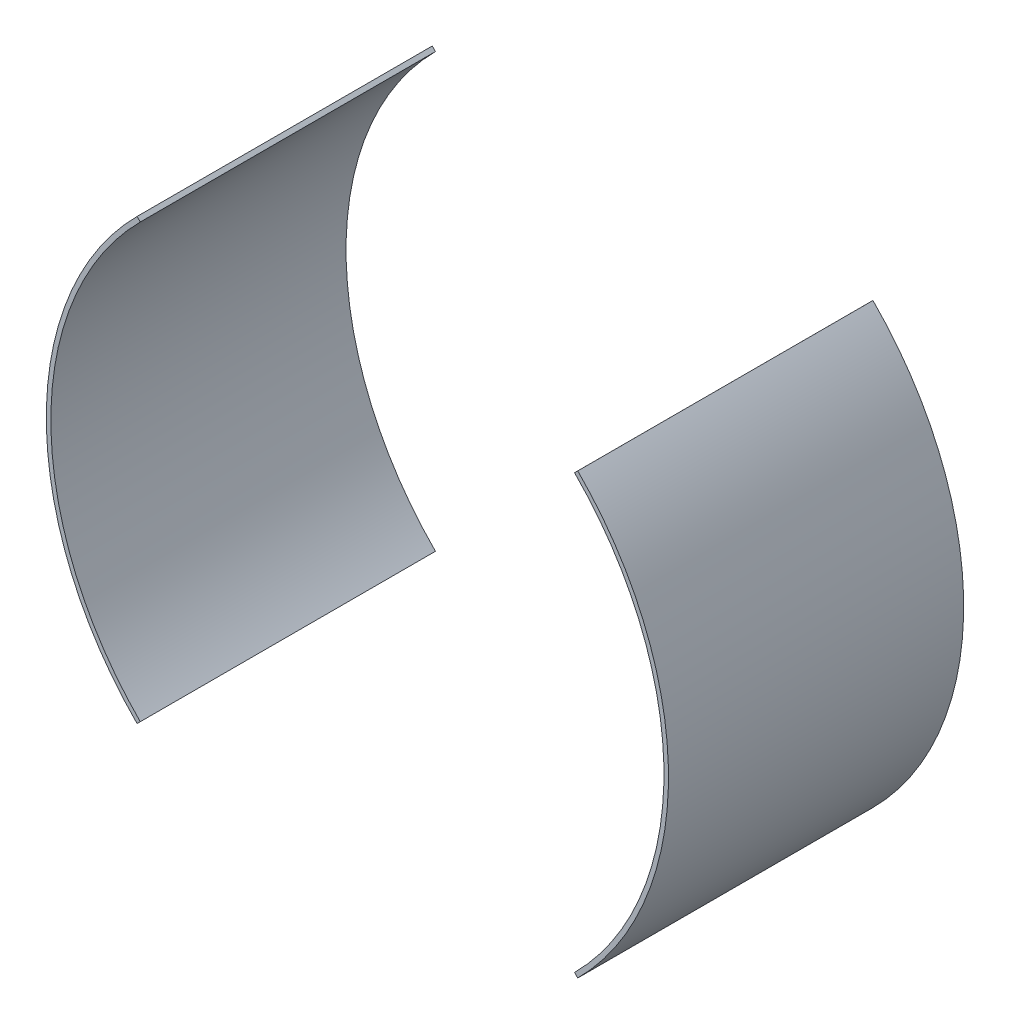
SolidWorks part; units mm, degrees
material "Brass"
ref_plane "Front Plane" through (0, 0, 0) normal (0, 0, 1) x (1, 0, 0)
ref_plane "Top Plane" through (0, 0, 0) normal (0, 1, 0) x (1, 0, 0)
ref_plane "Right Plane" through (0, 0, 0) normal (1, 0, 0) x (0, 0, -1)
sketch "Sketch1" plane through (0, 0, 0) normal (0, 0, 1) x (1, 0, 0)
  line L0 (0, 163.957) -> (0, -172.72) construction
  line L1 (-122.3426, 121.92) -> (-122.3426, -121.92) construction
  line L2 (122.3426, 121.92) -> (122.3426, -121.92) construction
  line L3 (-122.3426, 121.92) -> (122.3426, 121.92) construction
  line L4 (-122.3426, -121.92) -> (122.3426, -121.92) construction
  line L5 (-122.3426, 0) -> (122.3426, 0) construction
  arc A0 (-122.3426, 121.92) -> (-122.3426, -121.92) centre (0, 0) ccw
  arc A1 (122.3426, -121.92) -> (122.3426, 121.92) centre (0, 0) ccw
  circle A2 centre (0, 0) radius 15.9724 construction
  point P11 (0, 0)
  dimension "D1" = 345.44
  dimension "D2" = 243.84
extrude "Extrude-Thin1" add sketch "Sketch1" along normal blind 165.1 thin thin type mid plane wall 2.54
